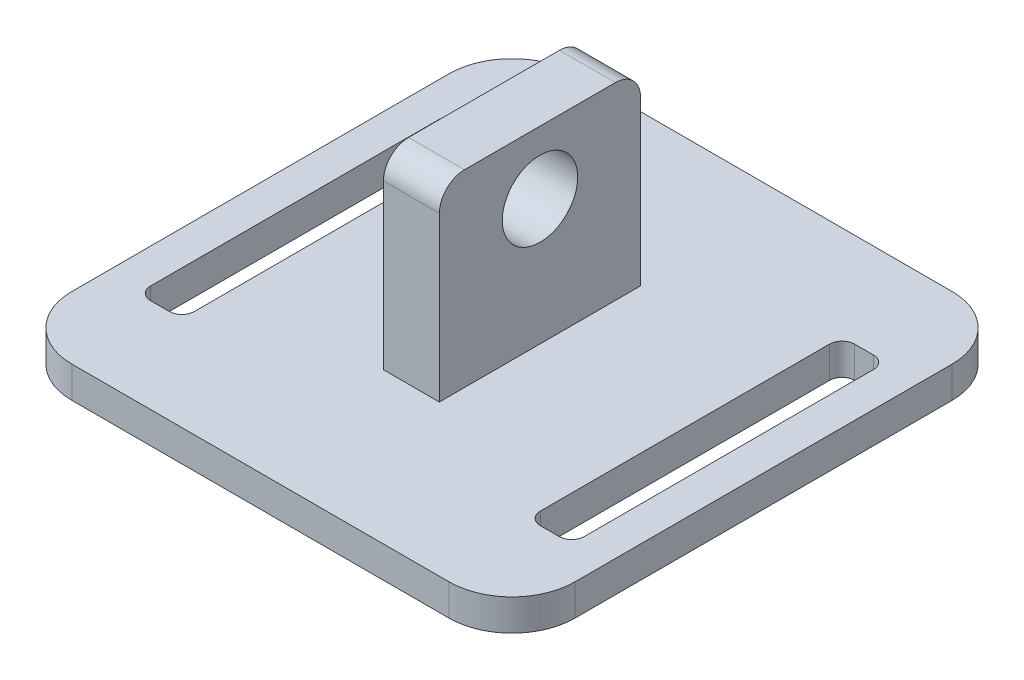
SolidWorks part; units mm, degrees
ref_plane "Front Plane" through (0, 0, 0) normal (0, 0, 1) x (1, 0, 0)
ref_plane "Top Plane" through (0, 0, 0) normal (0, 1, 0) x (1, 0, 0)
ref_plane "Right Plane" through (0, 0, 0) normal (1, 0, 0) x (0, 0, -1)
sketch "Sketch1" plane through (0, 0, 0) normal (0, 1, 0) x (1, 0, 0)
  line L0 (-20, 10.9375) -> (-17.25, 10.9375) construction
  line L1 (15, 20) -> (-15, 20)
  line L2 (20, 15) -> (20, -15)
  line L3 (15, -20) -> (-15, -20)
  line L4 (-20, 15) -> (-20, -15)
  line L5 (20, 20) -> (-20, -20) construction
  line L6 (20, -20) -> (-20, 20) construction
  line L7 (-17.25, 10.9375) -> (-13.75, 10.9375) construction
  line L8 (-15.5, 10.9375) -> (-15.5, 0.8828) construction
  line L9 (-20, 0) -> (30.8422, 0) construction
  line L10 (0, 15) -> (0, -29.8633) construction
  line L11 (-13.75, 12.5) -> (-17.25, 12.5)
  line L12 (-13.75, 12.5) -> (-13.75, -12.5)
  line L13 (-13.75, -12.5) -> (-17.25, -12.5)
  line L14 (-17.25, 12.5) -> (-17.25, -12.5)
  line L15 (-13.75, 12.5) -> (-17.25, -12.5) construction
  line L16 (-13.75, -12.5) -> (-17.25, 12.5) construction
  line L17 (13.75, -12.5) -> (17.25, -12.5)
  line L18 (17.25, 12.5) -> (17.25, -12.5)
  line L19 (13.75, 12.5) -> (17.25, 12.5)
  line L20 (13.75, 12.5) -> (13.75, -12.5)
  arc A0 (-15, -20) -> (-20, -15) centre (-15, -15) cw
  arc A1 (20, -15) -> (15, -20) centre (15, -15) cw
  arc A2 (15, 20) -> (20, 15) centre (15, 15) cw
  arc A3 (-15, 20) -> (-20, 15) centre (-15, 15) ccw
  point P0 (0, 0)
  point P25 (-15.5, 0)
  dimension "D3" = 5
  dimension "D1" = 40
  dimension "D2" = 40
  dimension "D4" = 2.75
  dimension "D5" = 3.5
  dimension "D6" = 25
extrude "Boss-Extrude1" add sketch "Sketch1" along normal blind 2.5
fillet "Fillet1" radius 1 4 edges at (-13.75, 1.25, 12.5) (-17.25, 1.25, 12.5) (-13.75, 1.25, -12.5) (-17.25, 1.25, -12.5)
fillet "Fillet2" radius 1 4 edges at (17.25, 1.25, -12.5) (13.75, 1.25, -12.5) (17.25, 1.25, 12.5) (13.75, 1.25, 12.5)
sketch "Sketch2" plane through (0, 2.5, 0) normal (0, 1, 0) x (1, 0, 0)
  line L1 (2.225, 8) -> (-2.225, 8)
  line L2 (2.225, 8) -> (2.225, -8)
  line L3 (2.225, -8) -> (-2.225, -8)
  line L4 (-2.225, 8) -> (-2.225, -8)
  line L5 (2.225, 8) -> (-2.225, -8) construction
  line L6 (2.225, -8) -> (-2.225, 8) construction
  point P0 (0, 0)
  dimension "D1" = 4.45
  dimension "D2" = 16
extrude "Boss-Extrude2" add sketch "Sketch2" along normal blind 15
sketch "Sketch3" plane through (-2.225, 0, 0) normal (-1, 0, 0) x (0, 0, 1)
  line L0 (0, 21.8052) -> (0, 6.5921) construction
  line L1 (-8, 17.5) -> (8, 17.5) construction
  circle A0 centre (0, 12.5) radius 3
  dimension "D2" = 6
  dimension "D1" = 5
extrude "Cut-Extrude1" cut sketch "Sketch3" against normal through all and the other way through all
fillet "Fillet3" radius 2 2 edges at (0, 17.5, 8) (0, 17.5, -8)
